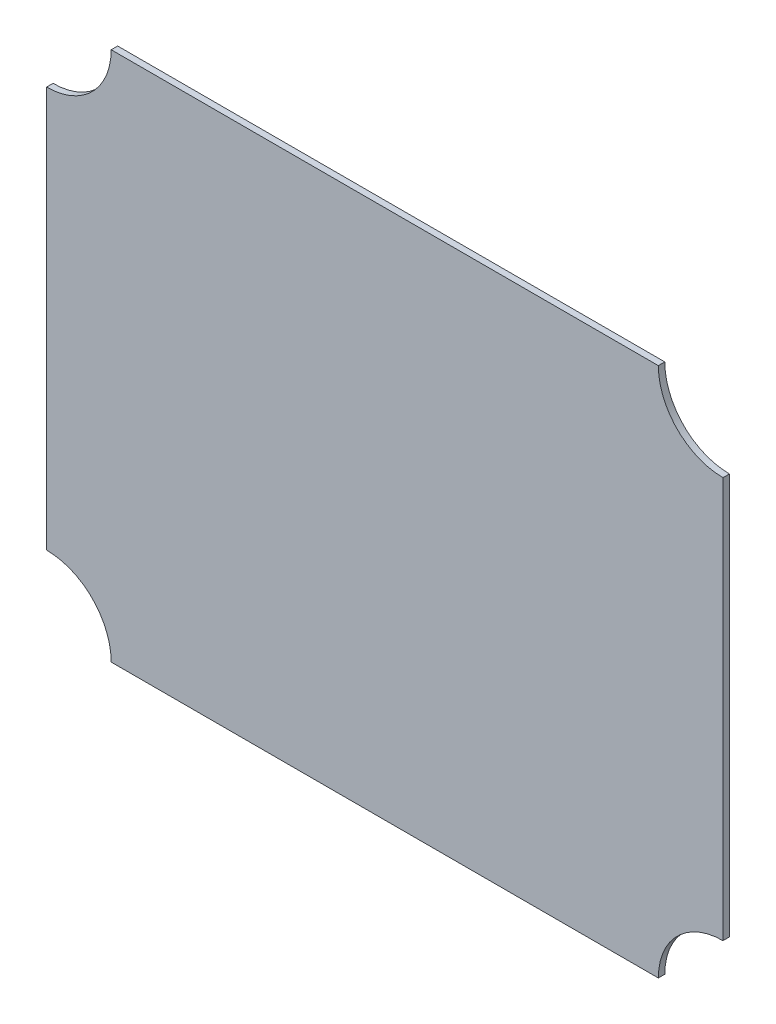
SolidWorks part; units mm, degrees
material "有机玻璃 (TM) GS 丙烯酸铸钣"
ref_plane "前视基准面" through (0, 0, 0) normal (0, 0, 1) x (1, 0, 0)
ref_plane "上视基准面" through (0, 0, 0) normal (0, 1, 0) x (1, 0, 0)
ref_plane "右视基准面" through (0, 0, 0) normal (1, 0, 0) x (0, 0, -1)
other "Configuration Table"
sketch "草图1" plane through (0, 0, 0) normal (0, 0, 1) x (1, 0, 0)
  line L0 (-365.3553, 0) -> (0, 0) construction
  line L1 (-211.5, 205) -> (211.5, 205)
  line L2 (-261.5, 155) -> (-261.5, -155)
  line L5 (261.5, 155) -> (261.5, -155)
  line L6 (-211.5, -205) -> (211.5, -205)
  line L7 (0, 287.0125) -> (0, -263.0229) construction
  arc A0 (-261.5, 155) -> (-211.5, 205) centre (-261.5, 205) ccw
  arc A1 (261.5, 155) -> (211.5, 205) centre (261.5, 205) cw
  arc A2 (261.5, -155) -> (211.5, -205) centre (261.5, -205) ccw
  arc A3 (-261.5, -155) -> (-211.5, -205) centre (-261.5, -205) cw
  point P0 (0, 0)
  point P3 (0, 205)
  point P10 (-261.5, 0)
  point P21 (0, -205)
  point P22 (261.5, 0)
  dimension "D3" = 50
  dimension "D1" = 205
  dimension "D4" = 261.5
extrude "凸台-拉伸1" add sketch "草图1" along normal mid plane 5
